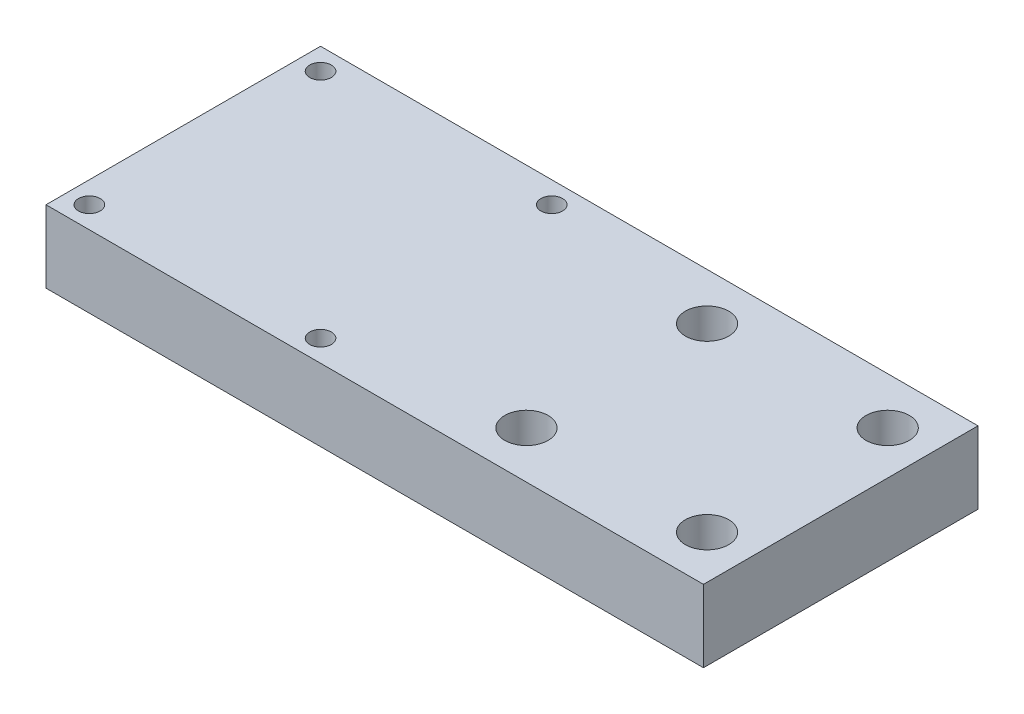
SolidWorks part; units mm, degrees
ref_plane "Front Plane" through (0, 0, 0) normal (0, 0, 1) x (1, 0, 0)
ref_plane "Top Plane" through (0, 0, 0) normal (0, 1, 0) x (1, 0, 0)
ref_plane "Right Plane" through (0, 0, 0) normal (1, 0, 0) x (0, 0, -1)
sketch "Sketch1" plane through (0, 0, 0) normal (0, 1, 0) x (1, 0, 0)
  line L1 (-18.9695, -35.3595) -> (72.0305, -35.3595)
  line L2 (-18.9695, -35.3595) -> (-18.9695, 2.6405)
  line L3 (-18.9695, 2.6405) -> (72.0305, 2.6405)
  line L4 (72.0305, -35.3595) -> (72.0305, 2.6405)
  line L5 (-15.9695, -0.3595) -> (16.0305, -0.3595) construction
  line L6 (-15.9695, -0.3595) -> (-15.9695, -32.3595) construction
  line L7 (-15.9695, -32.3595) -> (16.0305, -32.3595) construction
  line L8 (16.0305, -0.3595) -> (16.0305, -32.3595) construction
  circle A0 centre (-15.9695, -0.3595) radius 1.5
  circle A1 centre (16.0305, -0.3595) radius 1.5
  circle A2 centre (16.0305, -32.3595) radius 1.5
  circle A3 centre (-15.9695, -32.3595) radius 1.5
  circle A16 centre (41.0305, -28.8595) radius 3
  circle A17 centre (66.0305, -28.8595) radius 3
  circle A18 centre (41.0305, -3.8595) radius 3
  circle A19 centre (66.0305, -3.8595) radius 3
  dimension "D1" = 3
  dimension "D3" = 25
  dimension "D2" = 32
  dimension "D4" = 25
  dimension "D5" = 6
  dimension "D6" = 3
  dimension "D7" = 3
  dimension "D8" = 3
  dimension "D9" = 25
extrude "Boss-Extrude1" add sketch "Sketch1" along normal blind 10
